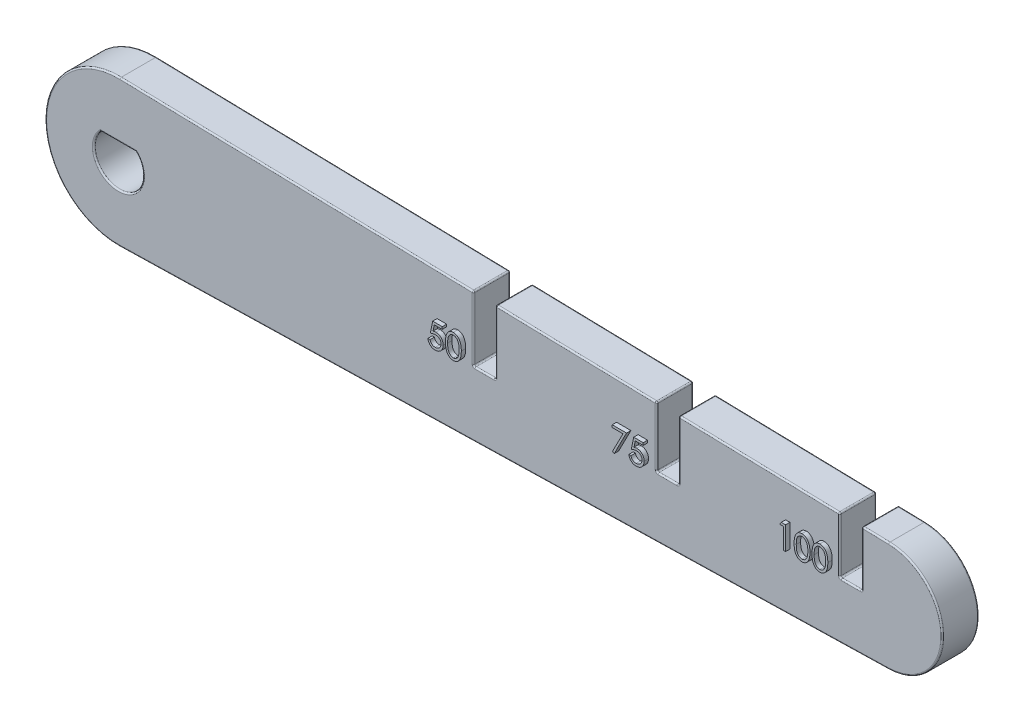
SolidWorks part; units mm, degrees
ref_plane "Front Plane" through (0, 0, 0) normal (0, 0, 1) x (1, 0, 0)
ref_plane "Top Plane" through (0, 0, 0) normal (0, 1, 0) x (1, 0, 0)
ref_plane "Right Plane" through (0, 0, 0) normal (1, 0, 0) x (0, 0, -1)
sketch "Sketch3" plane through (0, 0, 0) normal (0, 0, 1) x (1, 0, 0)
  line L0 (0.2381, 9.9972) -> (105.1786, 7.4979)
  line L1 (105.1786, -7.4979) -> (0.2381, -9.9972)
  arc A0 (0.2381, 9.9972) -> (0.2381, -9.9972) centre (0, 0) ccw
  arc A1 (105.1786, -7.4979) -> (105.1786, 7.4979) centre (105, 0) ccw
  point P9 (0, 0)
  point P10 (20.7794, -1.1947)
  point P11 (24.625, 0)
  dimension "D1" = 20
  dimension "D2" = 15
  dimension "D3" = 105
extrude "Boss-Extrude1" add sketch "Sketch3" along normal blind 5
sketch "Sketch2" plane through (0, 0, 0) normal (0, 0, 1) x (1, 0, 0)
  line L0 (-2.4, 2.3372) -> (2.4, 2.3372)
  arc A0 (2.4, 2.3372) -> (-2.4, 2.3372) centre (0, 0) cw
  dimension "D1" = 3.35
  dimension "D2" = 4.8
extrude "Cut-Extrude2" cut sketch "Sketch2" along normal up to next
sketch "Sketch4" plane through (0, 0, 5) normal (0, 0, 1) x (1, 0, 0)
  line L0 (105.1786, 7.4979) -> (0.2381, 9.9972) construction
  line L1 (98.5, 7.6569) -> (101.5, 7.6569)
  line L2 (98.5, 7.6569) -> (98.5, 0)
  line L3 (98.5, 0) -> (101.5, 0)
  line L4 (101.5, 7.6569) -> (101.5, 0)
  line L5 (100, 0) -> (100, 7.6212) construction
  line L6 (0, 0) -> (112.5, 0) construction
  line L7 (73.5, 8.2523) -> (76.5, 8.2523)
  line L8 (73.5, 8.2523) -> (73.5, 0)
  line L9 (73.5, 0) -> (76.5, 0)
  line L10 (76.5, 8.2523) -> (76.5, 0)
  line L11 (75, 0) -> (75, 8.2523) construction
  line L12 (48.5, 8.8477) -> (51.5, 8.8477)
  line L13 (48.5, 8.8477) -> (48.5, 0)
  line L14 (48.5, 0) -> (51.5, 0)
  line L15 (51.5, 8.8477) -> (51.5, 0)
  line L16 (50, 0) -> (50, 8.8477) construction
  arc A0 (105.1786, -7.4979) -> (105.1786, 7.4979) centre (105, 0) ccw construction
  point P8 (0, 0)
  point P27 (0, 0)
  point P28 (0, 0)
  point P29 (13.1528, 5.7381)
  point P30 (0, 0)
  point P31 (0, 0)
  point P32 (22.662, -2.2763)
  point P33 (41.6106, 7.1929)
  point P34 (19, 7.7503)
  point P35 (29, 7.1312)
  point P36 (0, 0)
  point P37 (30, 7.1312)
  point P38 (30, 6.539)
  point P39 (0, 0)
  point P40 (39, 6.0049)
  dimension "D3" = 3
  dimension "D4" = 50
  dimension "D5" = 75
  dimension "D6" = 100
extrude "Cut-Extrude3" cut sketch "Sketch4" against normal up to next
fillet "Fillet1" radius 0.2 48 edges at (51.5, 0, 2.5) (48.5, 0, 2.5) (101.5, 0, 2.5) (98.5, 0, 2.5) (76.5, 0, 2.5) (73.5, 0, 2.5) (0, 2.3372, 0) (0, -3.35, 0) (76.5, 4.0904, 0) (75, 0, 0) (73.5, 4.1262, 0) (62.5, 8.5143, 0) (51.5, 4.3881, 0) (50, 0, 0) (48.5, 4.4239, 0) (24.369, 9.4225, 0) (-10, 0, 0) (52.7083, -8.7475, 0) (112.5, 0, 0) (103.3393, 7.5417, 0) (101.5, 3.7927, 0) (100, 0, 0) (98.5, 3.8285, 0) (87.5, 7.9189, 0) (0, -3.35, 5) (0, 2.3372, 5) (100, 0, 5) (101.5, 3.7927, 5) (103.3393, 7.5417, 5) (112.5, 0, 5) (52.7083, -8.7475, 5) (-10, 0, 5) (24.369, 9.4225, 5) (48.5, 4.4239, 5) (50, 0, 5) (51.5, 4.3881, 5) (62.5, 8.5143, 5) (73.5, 4.1262, 5) (75, 0, 5) (76.5, 4.0904, 5) (87.5, 7.9189, 5) (98.5, 3.8285, 5) (101.5, 7.5855, 2.5) (98.5, 7.6569, 2.5) (76.5, 8.1809, 2.5) (73.5, 8.2523, 2.5) (51.5, 8.7763, 2.5) (48.5, 8.8477, 2.5)
sketch "Sketch5" plane through (0, 0, 5) normal (0, 0, 1) x (1, 0, 0)
  line L0 (0, 0) -> (112.3, 0) construction
  line L1 (48.5, 8.6525) -> (48.5, 0.2) construction
  line L2 (73.5, 8.057) -> (73.5, 0.2) construction
  line L3 (98.5, 7.4616) -> (98.5, 0.2) construction
  arc A0 (105.1738, -7.2979) -> (105.1738, 7.2979) centre (105, 0) ccw construction
  text T0 "50"
  text T1 "75"
  text T2 "100"
  point P1 (0, 0)
  point P7 (12.7627, 0)
  point P9 (0, 0)
  point P12 (23.7254, 0)
  point P13 (0, 0)
  point P14 (23.7844, 0.2)
  point P15 (22.9003, 0)
  point P17 (32.861, 0)
  dimension "D1" = 5.8
  dimension "D2" = 5.8
  dimension "D3" = 8.2
extrude "Boss-Extrude2" add sketch "Sketch5" along normal blind 0.6
